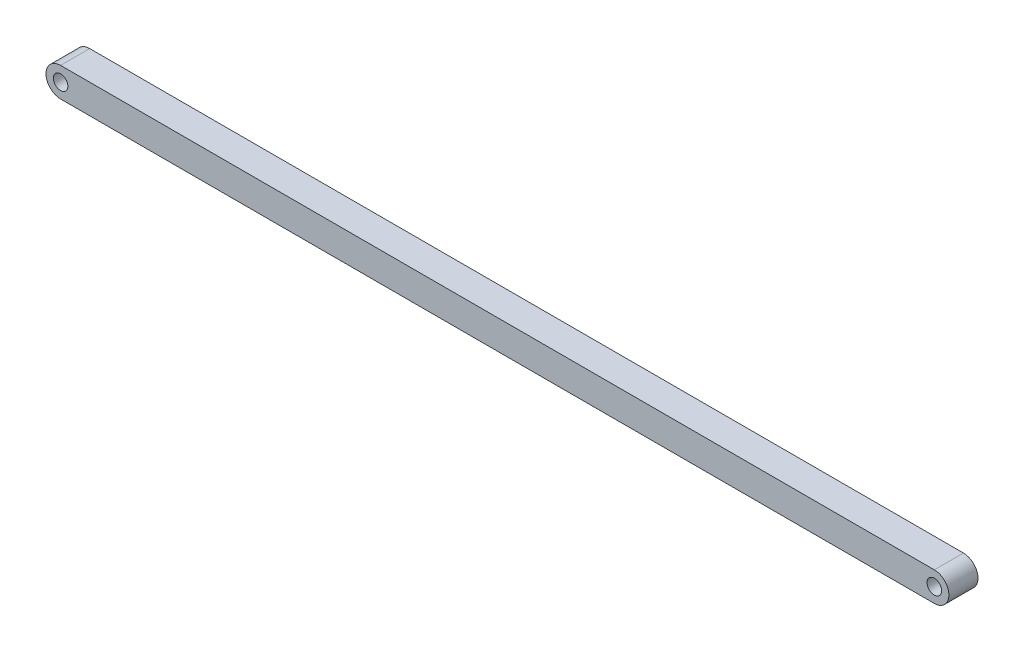
SolidWorks part; units mm, degrees
ref_plane "Front Plane" through (0, 0, 0) normal (0, 0, 1) x (1, 0, 0)
ref_plane "Top Plane" through (0, 0, 0) normal (0, 1, 0) x (1, 0, 0)
ref_plane "Right Plane" through (0, 0, 0) normal (1, 0, 0) x (0, 0, -1)
sketch "Sketch1" plane through (0, 0, 0) normal (0, 0, 1) x (1, 0, 0)
  line L0 (-75, 0) -> (75, 0) construction
  line L3 (-75, 2.5) -> (75, 2.5)
  line L4 (-75, -2.5) -> (75, -2.5)
  arc A2 (-75, 2.5) -> (-75, -2.5) centre (-75, 0) ccw
  arc A3 (75, -2.5) -> (75, 2.5) centre (75, 0) ccw
  circle A4 centre (-75, 0) radius 1.25
  circle A5 centre (75, 0) radius 1.25
  point P3 (0, 0)
  dimension "D1" = 2.5
  dimension "D2" = 2.5
  dimension "D3" = 5
  dimension "D4" = 150
extrude "Boss-Extrude1" add sketch "Sketch1" along normal blind 5
